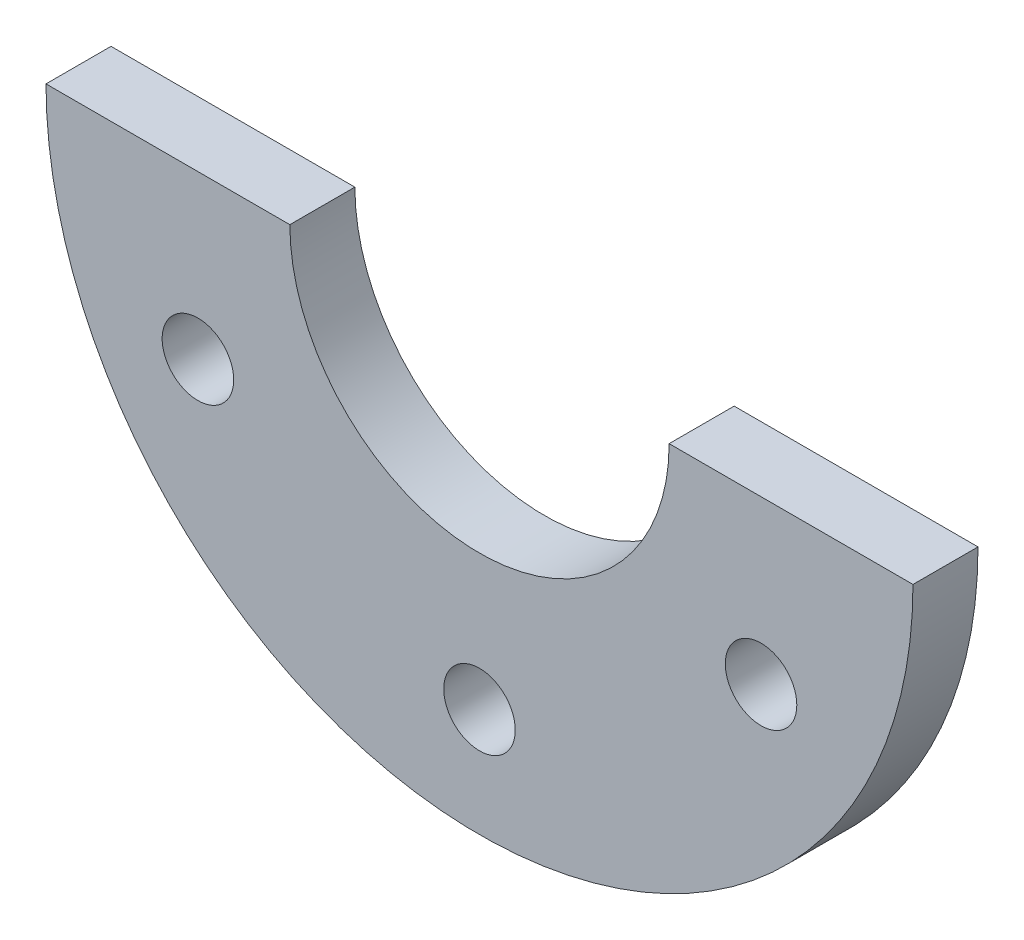
SolidWorks part; units mm, degrees
ref_plane "Front Plane" through (0, 0, 0) normal (0, 0, 1) x (1, 0, 0)
ref_plane "Top Plane" through (0, 0, 0) normal (0, 1, 0) x (1, 0, 0)
ref_plane "Right Plane" through (0, 0, 0) normal (1, 0, 0) x (0, 0, -1)
sketch "Sketch1" plane through (0, 0, 0) normal (0, 0, 1) x (1, 0, 0)
  line L0 (17.5, 0) -> (40, 0)
  line L3 (-40, 0) -> (-17.5, 0)
  arc A0 (-17.5, 0) -> (17.5, 0) centre (0, 0) ccw
  arc A1 (-40, 0) -> (40, 0) centre (0, 0) ccw
  point P3 (0, -20)
  dimension "D2" = 35
  dimension "D1" = 80
extrude "Boss-Extrude1" add sketch "Sketch1" along normal blind 6
sketch "Sketch2" plane through (0, 0, 0) normal (0, 0, 1) x (1, 0, 0)
  line L0 (0, -3.3) -> (0, 3.3) construction
  circle A0 centre (0, -30) radius 3.3
  circle A1 centre (-25.9808, -15) radius 3.3
  circle A5 centre (25.9808, -15) radius 3.3
  circle A6 centre (-25.9808, 15) radius 3.3 [skipped]
  circle A7 centre (0, 30) radius 3.3 [skipped]
  circle A8 centre (25.9808, 15) radius 3.3 [skipped]
  point P17 (0, 0)
  dimension "D1" = 6.6
  dimension "D2" = 30
  dimension "D3" = 6
extrude "Cut-Extrude2" cut sketch "Sketch2" along normal through all
